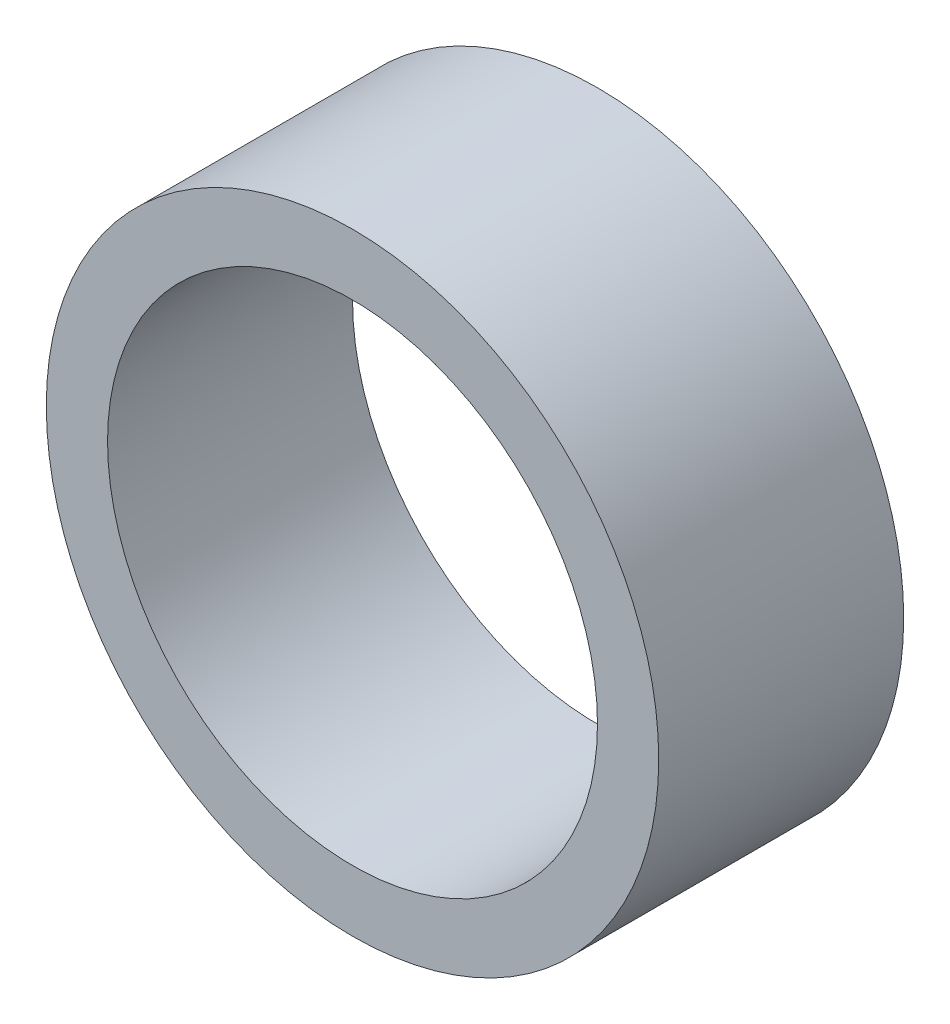
SolidWorks part; units mm, degrees
ref_plane "Front Plane" through (0, 0, 0) normal (1, 0, 0) x (0, 1, 0)
ref_plane "Top Plane" through (0, 0, 0) normal (0, 0, 1) x (0, 1, 0)
ref_plane "Right Plane" through (0, 0, 0) normal (0, 1, 0) x (-1, 0, 0)
sketch "Sketch1" plane through (0, 0, 0) normal (0, 0, 1) x (0, 1, 0)
  circle A0 centre (0, 0) radius 6.25
  circle A1 centre (0, 0) radius 5
  dimension "D1" = 12.5
  dimension "D2" = 10
extrude "Boss-Extrude1" add sketch "Sketch1" along normal blind 5
